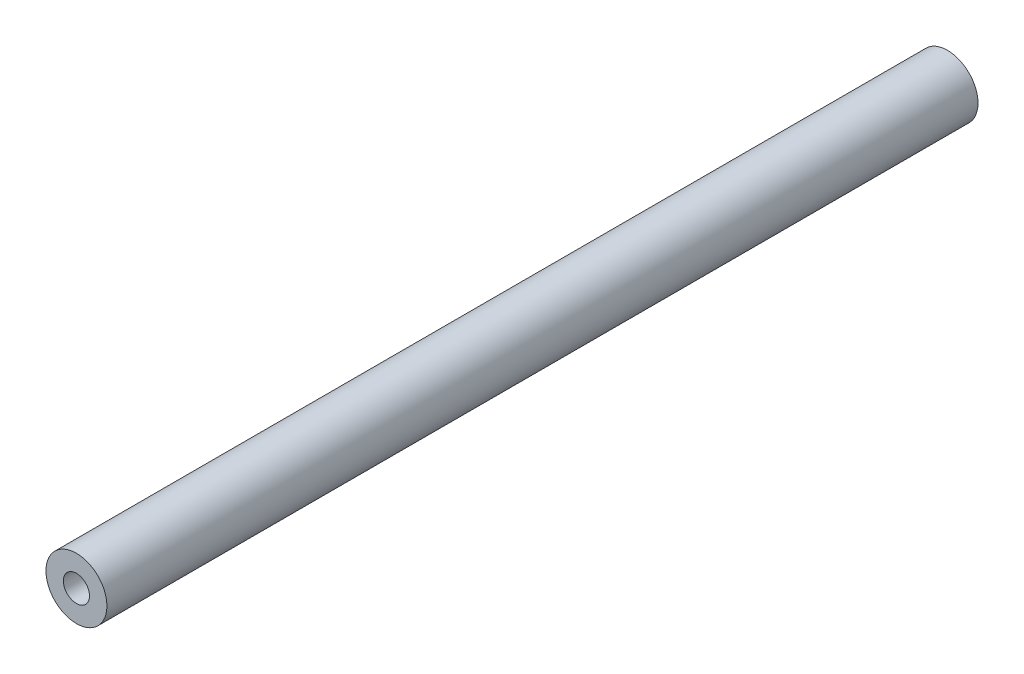
SolidWorks part; units mm, degrees
ref_plane "Front Plane" through (0, 0, 0) normal (0, 0, 1) x (1, 0, 0)
ref_plane "Top Plane" through (0, 0, 0) normal (0, 1, 0) x (1, 0, 0)
ref_plane "Right Plane" through (0, 0, 0) normal (1, 0, 0) x (0, 0, -1)
sketch "Sketch1" plane through (0, 0, 0) normal (0, 0, 1) x (1, 0, 0)
  circle A0 centre (0, 0) radius 3.5
  circle A1 centre (0, 0) radius 1.5
  dimension "D1" = 7
  dimension "D2" = 3
extrude "Boss-Extrude1" add sketch "Sketch1" along normal blind 100
